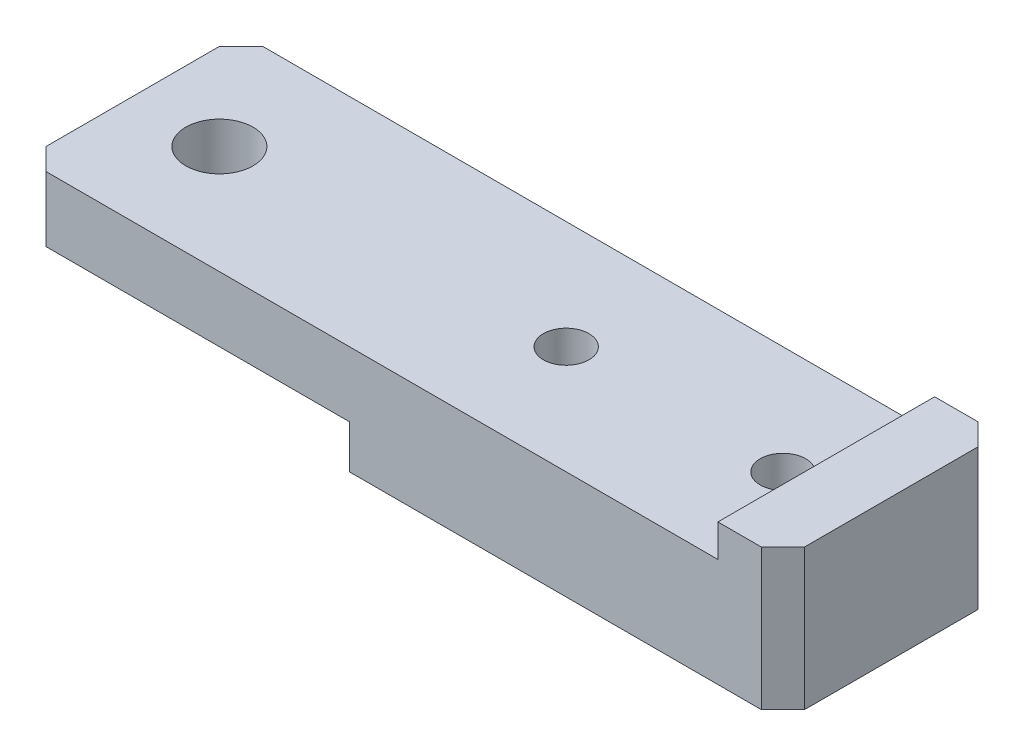
SolidWorks part; units mm, degrees
ref_plane "前视基准面" through (0, 0, 0) normal (0, 0, 1) x (1, 0, 0)
ref_plane "上视基准面" through (0, 0, 0) normal (0, 1, 0) x (1, 0, 0)
ref_plane "右视基准面" through (0, 0, 0) normal (1, 0, 0) x (0, 0, -1)
other "Configuration Table"
sketch "草图1" plane through (0, 0, 0) normal (0, 0, 1) x (1, 0, 0)
  line L0 (0, 6) -> (0, 12)
  line L1 (0, 12) -> (64, 12)
  line L2 (70, 12) -> (70, 2)
  line L3 (70, 2) -> (30, 2)
  line L4 (0, 6) -> (30, 6)
  line L5 (30, 6) -> (30, 2)
  line L6 (0, 6) -> (0, 0) construction
  line L8 (70, 15) -> (64, 15)
  line L9 (64, 15) -> (64, 12)
  line L10 (70, 15) -> (70, 12)
  dimension "D1" = 15
  dimension "D2" = 6
  dimension "D3" = 70
  dimension "D4" = 12
  dimension "D5" = 30
  dimension "D6" = 2
  dimension "D7" = 6
extrude "凸台-拉伸1" add sketch "草图1" along normal mid plane 20
sketch "草图3" plane through (0, 6, 0) normal (0, -1, 0) x (1, 0, 0)
  circle A0 centre (8, 0) radius 5
  dimension "D1" = 10
  dimension "D2" = 8
extrude "凸台-拉伸2" add sketch "草图3" along normal blind 4
chamfer "倒角1" distance 2 angle 45 2 edges at (0, 9, -10) (0, 9, 10)
chamfer "倒角2" distance 2 angle 45 2 edges at (70, 8.5, -10) (70, 8.5, 10)
sketch "草图4" plane through (0, 2, 0) normal (0, -1, 0) x (1, 0, 0)
  line L0 (70, 8) -> (70, -8) construction
  circle A0 centre (40, 0) radius 2.1
  circle A1 centre (60, 0) radius 2.1
  circle A2 centre (8, 0) radius 3.1
  dimension "D2" = 6.2
  dimension "D3" = 4.2
  dimension "D4" = 4.2
  dimension "D1" = 20
  dimension "D5" = 10
extrude "切除-拉伸1" cut sketch "草图4" against normal through all
fillet "圆角1" radius 1 1 edges at (8, 6, 5)
